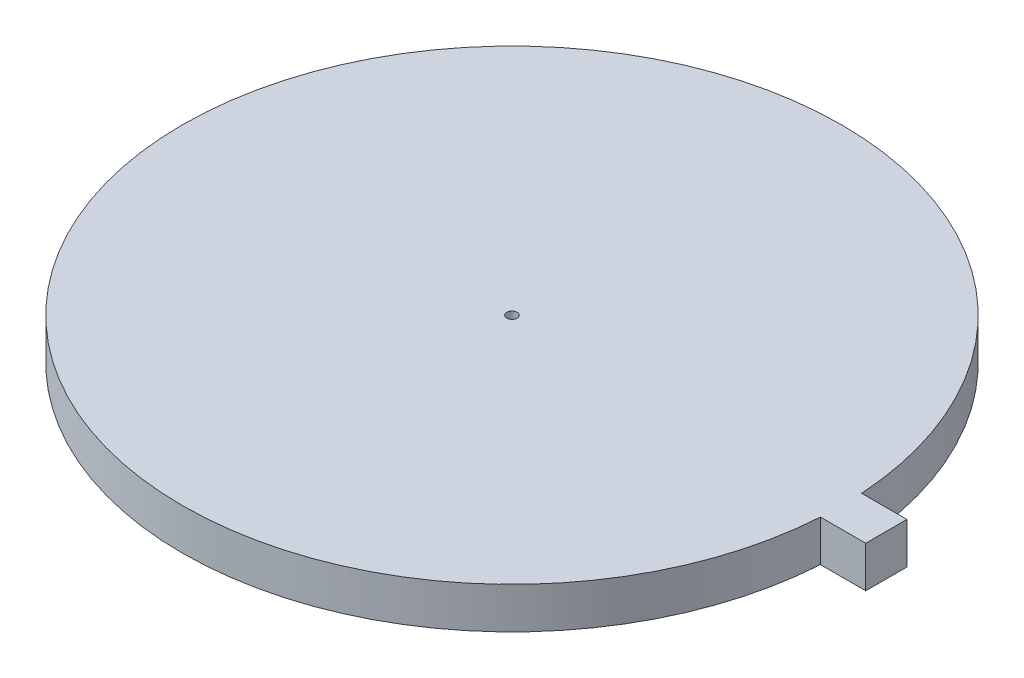
SolidWorks part; units mm, degrees
material "ABS"
ref_plane "Front Plane" through (0, 0, 0) normal (0, 0, 1) x (1, 0, 0)
ref_plane "Top Plane" through (0, 0, 0) normal (0, 1, 0) x (1, 0, 0)
ref_plane "Right Plane" through (0, 0, 0) normal (1, 0, 0) x (0, 0, -1)
other "Bounding Box"
ref_plane "Default Plane" through (-142.0748, 0, 21.4445) normal (0.5937, 0, -0.8047) x (-0.8047, 0, -0.5937)
sketch "Sketch1" plane through (0, 0, 0) normal (0, 1, 0) x (1, 0, 0)
  line L1 (115.3714, -3.175) -> (115.3714, 6.35)
  line L2 (115.3714, -3.175) -> (115.3714, -6.35)
  line L3 (115.3714, 6.35) -> (101.4014, 6.35)
  line L4 (115.3714, -6.35) -> (101.4014, -6.35)
  circle A0 centre (0, 0) radius 1.5875
  arc A1 (101.4014, 6.35) -> (101.4014, -6.35) centre (0, 0) ccw
  dimension "D1" = 3.175
  dimension "D2" = 203.2
  dimension "D3" = 12.7
  dimension "D4" = 13.97
  dimension "D5" = 13.97
extrude "Boss-Extrude1" add sketch "Sketch1" along normal blind 12.7 contours A1 L4 L2 L1 L3 | A0
